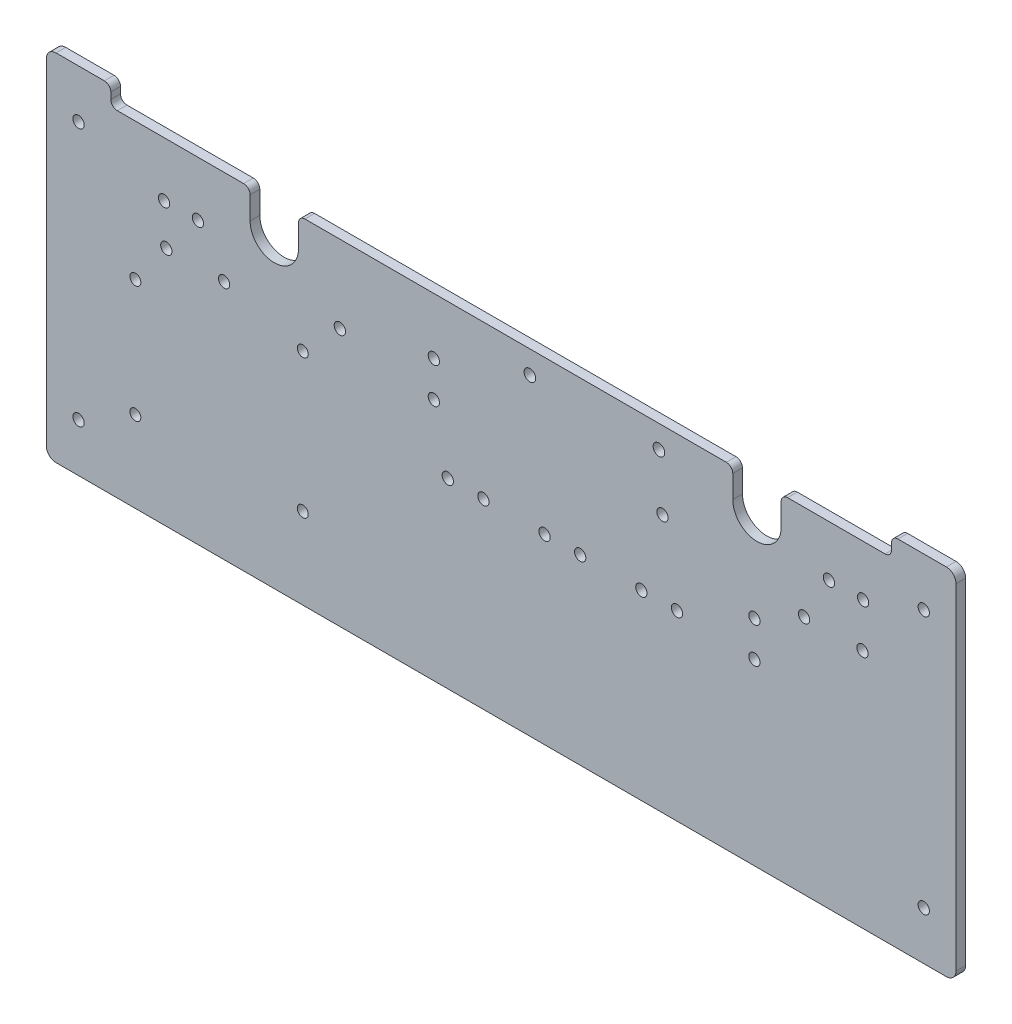
SolidWorks part; units mm, degrees
ref_plane "Front Plane" through (0, 0, 0) normal (0, 0, 1) x (1, 0, 0)
ref_plane "Top Plane" through (0, 0, 0) normal (0, 1, 0) x (1, 0, 0)
ref_plane "Right Plane" through (0, 0, 0) normal (1, 0, 0) x (0, 0, -1)
sketch "Sketch1" plane through (0, 0, 0) normal (0, 0, 1) x (1, 0, 0)
  line L0 (-70.3259, 334) -> (-70.3259, 319) construction
  line L1 (-138, 334) -> (-123, 334)
  line L2 (-141, 331) -> (-141, 227)
  line L3 (-138, 224) -> (138, 224)
  line L4 (141, 331) -> (141, 227)
  line L5 (-131, 324.882) -> (-131, 322.9262) construction
  line L6 (131, 227.3054) -> (131, 228.2548) construction
  line L7 (-62.8259, 326) -> (-62.8259, 319)
  line L8 (-77.8259, 326) -> (-77.8259, 319)
  line L10 (79.2994, 334) -> (79.2994, 319) construction
  line L11 (86.7994, 326) -> (86.7994, 319)
  line L12 (71.7994, 326) -> (71.7994, 319)
  line L13 (123, 334) -> (138, 334)
  line L14 (-121, 332) -> (-121, 330)
  line L15 (-119, 328) -> (-79.8259, 328)
  line L16 (121, 330) -> (121, 332)
  line L17 (88.7994, 328) -> (119, 328)
  line L18 (-60.8259, 328) -> (69.7994, 328)
  arc A0 (-141, 227) -> (-138, 224) centre (-138, 227) ccw
  arc A1 (-138, 334) -> (-141, 331) centre (-138, 331) ccw
  arc A2 (138, 224) -> (141, 227) centre (138, 227) ccw
  arc A3 (138, 334) -> (141, 331) centre (138, 331) cw
  circle A4 centre (-131, 319) radius 1.75
  circle A5 centre (-131, 239) radius 1.75
  circle A6 centre (131, 319) radius 1.75
  circle A7 centre (131, 239) radius 1.75
  arc A9 (-77.8259, 319) -> (-62.8259, 319) centre (-70.3259, 319) ccw
  arc A13 (71.7994, 319) -> (86.7994, 319) centre (79.2994, 319) ccw
  circle A16 centre (-104.5, 311.05) radius 1.75
  circle A17 centre (-94, 311.05) radius 1.75
  circle A18 centre (-103.8, 298.65) radius 1.75
  circle A19 centre (-85.9, 298.65) radius 1.75
  circle A20 centre (101.6, 312.25) radius 1.75
  circle A21 centre (112.2, 312.25) radius 1.75
  circle A22 centre (93.9, 298.55) radius 1.75
  circle A23 centre (112, 298.55) radius 1.75
  arc A24 (119, 328) -> (121, 330) centre (119, 330) ccw
  arc A25 (121, 332) -> (123, 334) centre (123, 332) cw
  arc A26 (-121, 330) -> (-119, 328) centre (-119, 330) ccw
  arc A27 (-121, 332) -> (-123, 334) centre (-123, 332) ccw
  arc A28 (86.7994, 326) -> (88.7994, 328) centre (88.7994, 326) cw
  arc A29 (71.7994, 326) -> (69.7994, 328) centre (69.7994, 326) ccw
  arc A30 (-62.8259, 326) -> (-60.8259, 328) centre (-60.8259, 326) cw
  arc A31 (-77.8259, 326) -> (-79.8259, 328) centre (-79.8259, 326) ccw
  circle A32 centre (-50, 304) radius 1.75
  circle A33 centre (50, 304) radius 1.75
  circle A34 centre (8.9101, 320.94) radius 1.8
  circle A35 centre (48.9101, 320.94) radius 1.8
  circle A36 centre (-113.4, 285.5) radius 1.7
  circle A37 centre (-16.54, 280.5) radius 1.75
  circle A38 centre (-5.5, 280.5) radius 1.75
  circle A39 centre (13.46, 280.5) radius 1.75
  circle A40 centre (-113.4, 249.2) radius 1.7
  circle A41 centre (-61.5, 249.2) radius 1.7
  circle A42 centre (-61.5, 292.2) radius 1.7
  circle A43 centre (24.5, 280.5) radius 1.75
  circle A44 centre (43.46, 280.5) radius 1.75
  circle A45 centre (54.5, 280.5) radius 1.75
  circle A46 centre (-20.8709, 310.54) radius 1.75
  circle A47 centre (-20.8709, 299.5) radius 1.75
  circle A48 centre (78.5, 290.5) radius 1.75
  circle A49 centre (78.5, 279.46) radius 1.75
  point P8 (-141, 334)
  point P11 (141, 224)
  point P14 (141, 334)
  point P29 (-69.3016, 326.5)
  point P34 (76.7994, 326.5)
  point P71 (86.7994, 328)
  point P76 (-62.8259, 328)
  point P86 (0, 224)
  point P116 (0, 0)
  point P117 (0, 0)
  point P118 (0, 0)
  dimension "D3" = 3
  dimension "D4" = 3.5
  dimension "D5" = 15
  dimension "D6" = 3.5
  dimension "D7" = 15
  dimension "D8" = 3.5
  dimension "D9" = 15
  dimension "D10" = 3.5
  dimension "D11" = 15
  dimension "D14" = 2
  dimension "D16" = 15
  dimension "D17" = 2
  dimension "D18" = 3.5
  dimension "D19" = 3.5
  dimension "D20" = 3.5
  dimension "D21" = 3.5
  dimension "D22" = 3.5
  dimension "D23" = 3.5
  dimension "D24" = 3.5
  dimension "D25" = 3.5
  dimension "D30" = 3.5
  dimension "D31" = 3.5
  dimension "D32" = 100
  dimension "D33" = 50
  dimension "D34" = 80
  dimension "D35" = 3.6
  dimension "D36" = 3.6
  dimension "D37" = 3.4
  dimension "D38" = 3.4
  dimension "D39" = 3.4
  dimension "D40" = 3.4
  dimension "D41" = 3.5
  dimension "D42" = 3.5
  dimension "D43" = 3.5
  dimension "D44" = 3.5
  dimension "D45" = 3.5
  dimension "D46" = 3.5
  dimension "D47" = 3.5
  dimension "D48" = 3.5
  dimension "D49" = 3.5
  dimension "D50" = 3.5
  dimension "D1" = 110
  dimension "D2" = 282
  dimension "D12" = 15
  dimension "D13" = 15
  dimension "D15" = 15
  dimension "D26" = 15
  dimension "D27" = 6
  dimension "D28" = 20
  dimension "D29" = 20
extrude "Boss-Extrude1" add sketch "Sketch1" along normal blind 3
